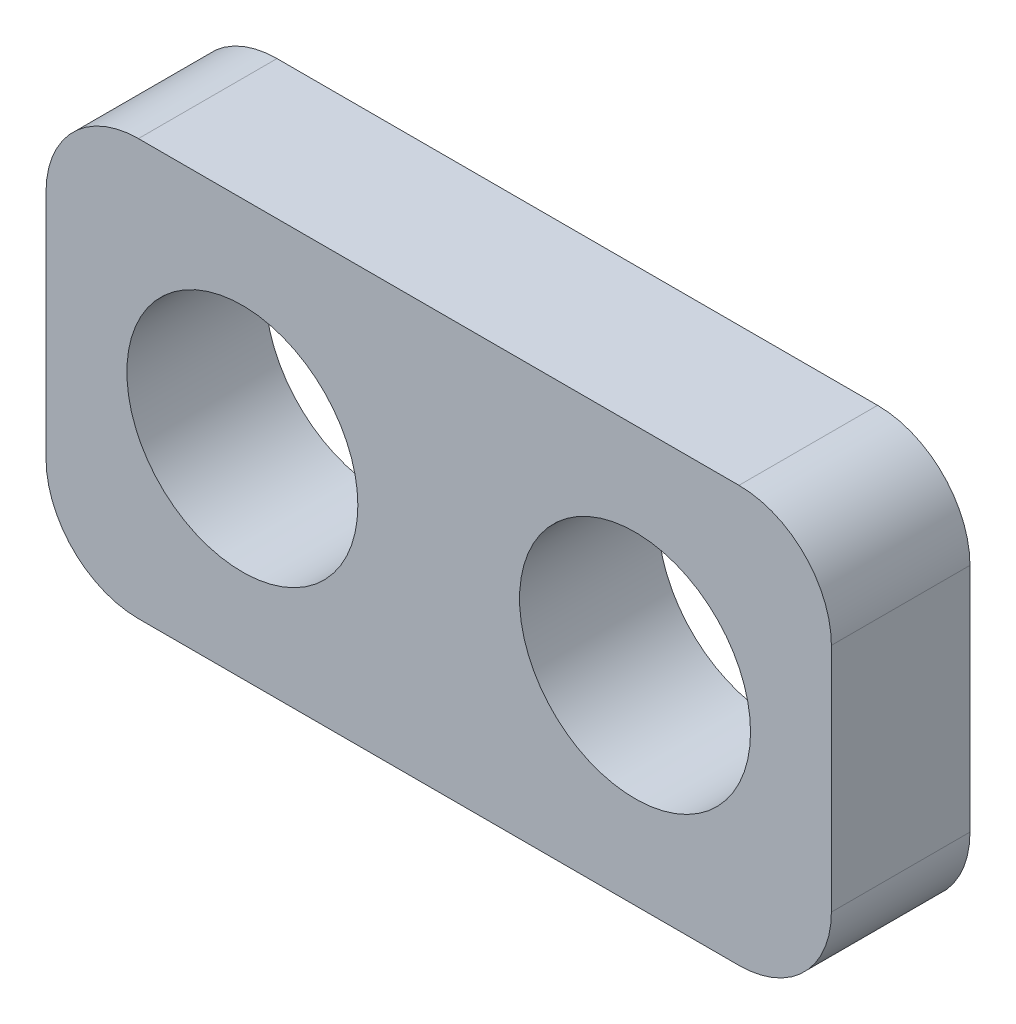
SolidWorks part; units mm, degrees
ref_plane "Front Plane" through (0, 0, 0) normal (0, 0, 1) x (1, 0, 0)
ref_plane "Top Plane" through (0, 0, 0) normal (0, 1, 0) x (1, 0, 0)
ref_plane "Right Plane" through (0, 0, 0) normal (1, 0, 0) x (0, 0, -1)
sketch "Sketch1" plane through (0, 0, 0) normal (0, 0, 1) x (1, 0, 0)
  line L0 (0, 0) -> (-8.5, 0) construction
  line L1 (-6.5, -4.5) -> (6.5, -4.5)
  line L2 (-8.5, -2.5) -> (-8.5, 2.5)
  line L3 (-6.5, 4.5) -> (6.5, 4.5)
  line L4 (8.5, -2.5) -> (8.5, 2.5)
  line L5 (0, 0) -> (8.5, 0) construction
  line L6 (0, 4.5) -> (0, -4.5) construction
  circle A0 centre (-4.25, 0) radius 2.5
  circle A1 centre (4.25, 0) radius 2.5
  arc A2 (6.5, 4.5) -> (8.5, 2.5) centre (6.5, 2.5) cw
  arc A3 (6.5, -4.5) -> (8.5, -2.5) centre (6.5, -2.5) ccw
  arc A4 (-6.5, -4.5) -> (-8.5, -2.5) centre (-6.5, -2.5) cw
  arc A5 (-8.5, 2.5) -> (-6.5, 4.5) centre (-6.5, 2.5) cw
  point P0 (0, 0)
  point P17 (8.5, 4.5)
  point P22 (-8.5, -4.5)
  point P25 (-8.5, 4.5)
  dimension "D3" = 2
  dimension "D1" = 17
  dimension "D2" = 9
extrude "Boss-Extrude1" add sketch "Sketch1" along normal blind 3
